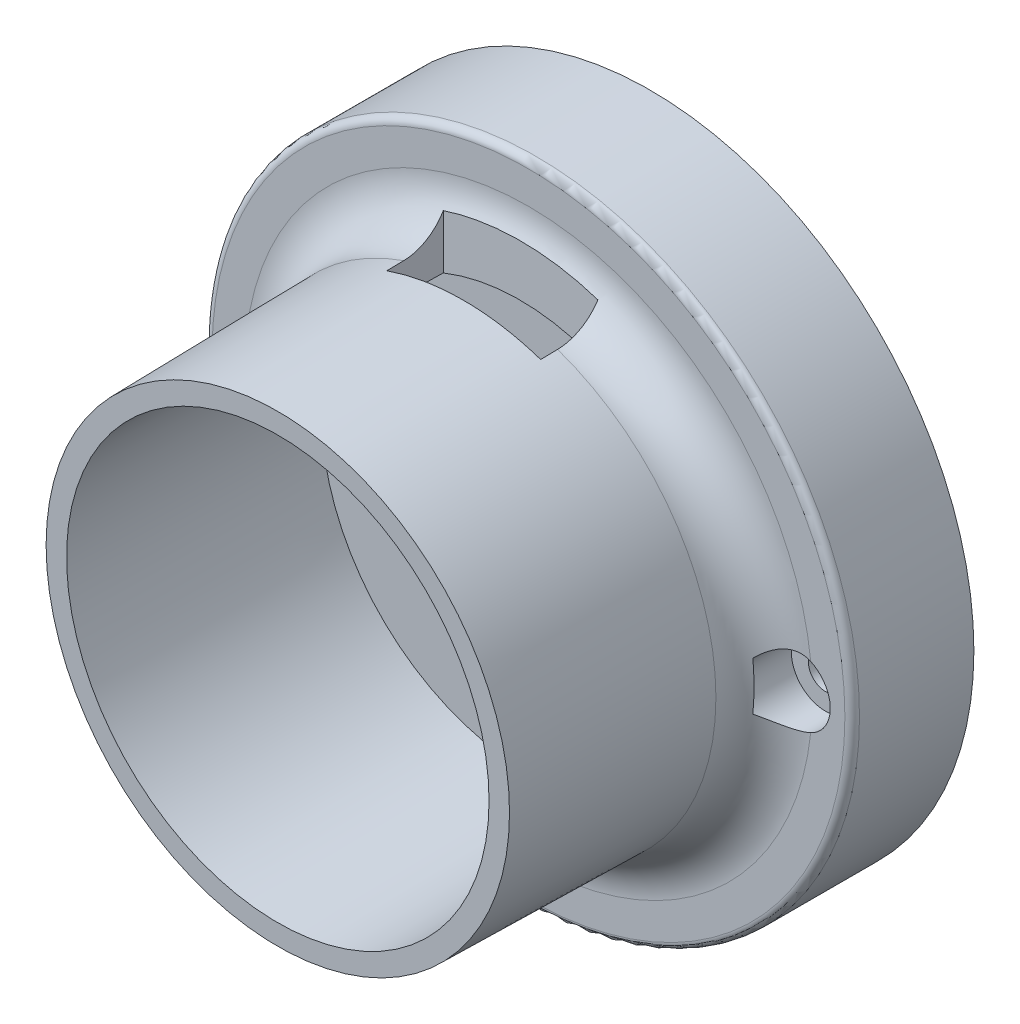
SolidWorks part; units mm, degrees
ref_plane "Front Plane" through (0, 0, 0) normal (0, 0, 1) x (1, 0, 0)
ref_plane "Top Plane" through (0, 0, 0) normal (0, 1, 0) x (1, 0, 0)
ref_plane "Right Plane" through (0, 0, 0) normal (1, 0, 0) x (0, 0, -1)
sketch "Sketch1" plane through (0, 0, 0) normal (0, 0, 1) x (1, 0, 0)
  circle A0 centre (0, 0) radius 12.1
  circle A1 centre (0, 0) radius 13.3
  dimension "D1" = 24.2
  dimension "D2" = 1.2
extrude "Boss-Extrude1" add sketch "Sketch1" along normal blind 3
sketch "Sketch2" plane through (0, 0, 3) normal (0, 0, 1) x (1, 0, 0)
  circle A1 centre (0, 0) radius 13.3
  circle A2 centre (0, 0) radius 13.3
  dimension "D1" = 0
extrude "Boss-Extrude2" add sketch "Sketch2" along normal blind 2
sketch "Sketch3" plane through (0, 0, 5) normal (0, 0, 1) x (1, 0, 0)
  circle A0 centre (0, 0) radius 4
  dimension "D1" = 8
extrude "Cut-Extrude1" cut sketch "Sketch3" against normal blind 10.2
sketch "Sketch4" plane through (0, 0, 5) normal (0, 0, 1) x (1, 0, 0)
  circle A0 centre (0, 0) radius 8.5
  circle A1 centre (0, 0) radius 9.7
  dimension "D1" = 17
  dimension "D2" = 1.2
extrude "Boss-Extrude3" add sketch "Sketch4" along normal blind 10.3 draft 1
fillet "Fillet1" radius 2 1 edges at (9.7, 0, 5)
sketch "Sketch5" plane through (0, 0, 3) normal (0, 0, -1) x (-1, 0, 0)
  circle A0 centre (0, 0) radius 9
  circle A1 centre (0, 0) radius 4 construction
  circle A2 centre (0, 0) radius 4
  dimension "D1" = 18
extrude "Boss-Extrude4" add sketch "Sketch5" along normal blind 0.8 draft 1
sketch "Sketch6" plane through (0, 0, 0) normal (0, 0, -1) x (-1, 0, 0)
  line L0 (0, 0) -> (0, 11.2) construction
  line L1 (3.0296, 11.7146) -> (2.8043, 10.8433)
  line L2 (-3.0296, 11.7146) -> (-2.8043, 10.8433)
  circle A0 centre (0, 0) radius 12.1 construction
  arc A1 (3.0296, 11.7146) -> (-3.0296, 11.7146) centre (0, 0) ccw
  arc A2 (2.8043, 10.8433) -> (-2.8043, 10.8433) centre (0, 0) ccw
  circle A4 centre (0, 0) radius 11.2 construction
  circle A5 centre (0, 0) radius 12.1 construction
  point P4 (11.5713, 3.5377)
  point P7 (13, 0)
  dimension "D2" = 14.5
  dimension "D3" = 14.5
  dimension "D1" = 0.9
extrude "Boss-Extrude5" add sketch "Sketch6" against normal up to surface (3 mm away) up to face at (12.1, 0, 3)
fillet "Fillet2" radius 0.1 4 edges at (-3.0296, 11.7146, 1.5) (3.0296, 11.7146, 1.5) (-2.8043, 10.8433, 1.5) (2.8043, 10.8433, 1.5)
sketch "Sketch7" plane through (0, 0, 0) normal (0, 1, 0) x (1, 0, 0)
  line L0 (-11.6654, -5) -> (11.6654, -5) construction
  line L1 (-11.6654, -5) -> (11.6654, -5) construction
  line L3 (-3, -7.5) -> (3, -7.5)
  line L4 (-3, -7.5) -> (-3, -5.5)
  line L5 (-3, -5.5) -> (3, -5.5)
  line L6 (3, -7.5) -> (3, -5.5)
  point P6 (0, -5.5)
  dimension "D1" = 0.5
  dimension "D2" = 6
  dimension "D3" = 2
extrude "Cut-Extrude2" cut sketch "Sketch7" along normal blind 20.8 draft 1 draft outward yes
sketch "Sketch8" plane through (0, 0, 3) normal (0, 0, -1) x (-1, 0, 0)
  line L0 (0, 0) -> (0, 19.6851) construction
  line L1 (0, 0) -> (-11, 0) construction
  circle A0 centre (-11, 0) radius 0.7
  circle A1 centre (11, 0) radius 0.7
  dimension "D1" = 11
  dimension "D2" = 1.4
extrude "Cut-Extrude3" cut sketch "Sketch8" against normal blind 20.8
sketch "Sketch9" plane through (0, 0, 3) normal (0, 0, -1) x (-1, 0, 0)
  circle A2 centre (-11, 0) radius 1.4
  circle A3 centre (-11, 0) radius 1.4
  circle A5 centre (11, 0) radius 1.5
  circle A6 centre (11, 0) radius 1.5
  dimension "D1" = 0.7
  dimension "D2" = 0.8
extrude "Cut-Extrude4" cut sketch "Sketch9" against normal blind 2 from offset 0.8 offset against normal yes
fillet "Fillet3" radius 0.3 1 edges at (13.3, 0, 5)
